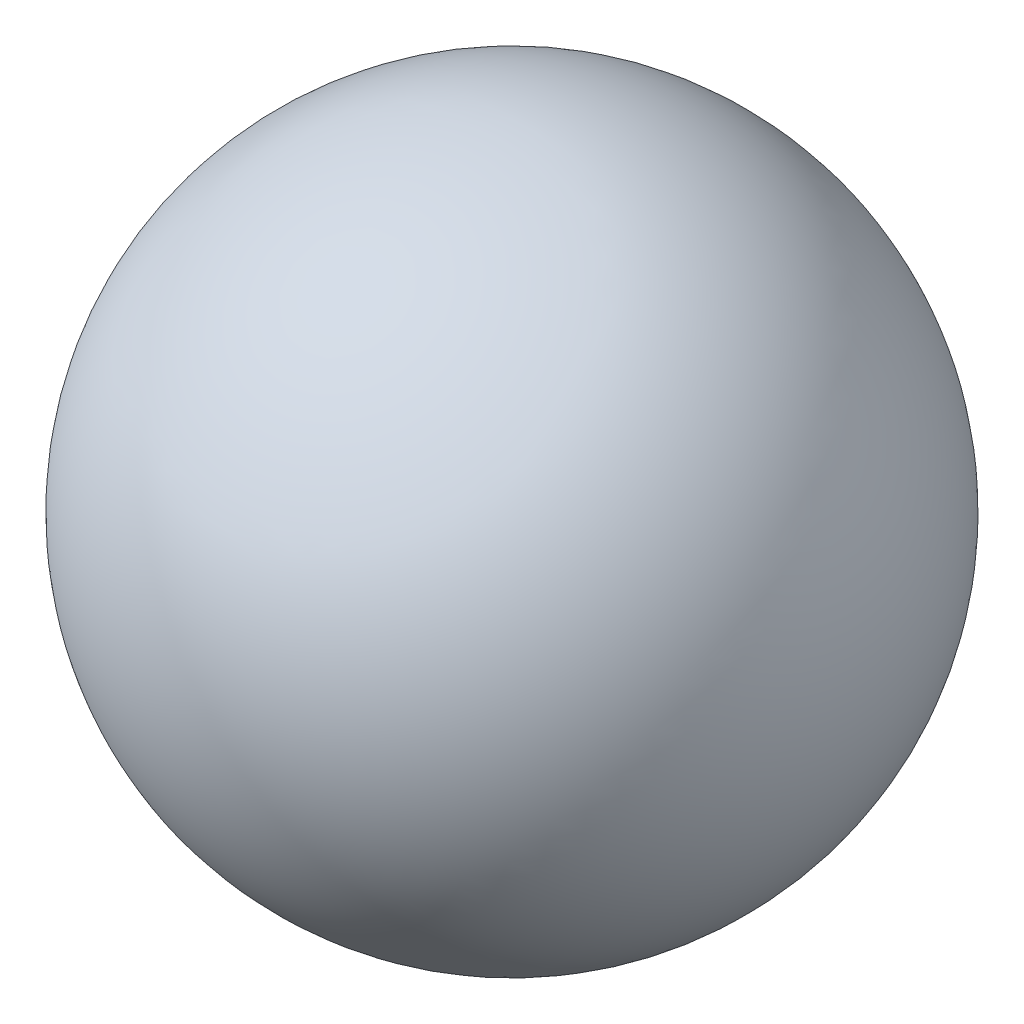
SolidWorks part; units mm, degrees
material "合金钢"
ref_plane "前视基准面" through (0, 0, 0) normal (0, 0, 1) x (1, 0, 0)
ref_plane "上视基准面" through (0, 0, 0) normal (0, 1, 0) x (1, 0, 0)
ref_plane "右视基准面" through (0, 0, 0) normal (1, 0, 0) x (0, 0, -1)
sketch "草图1" plane through (0, 0, 0) normal (0, 1, 0) x (1, 0, 0)
  line L0 (0, 12.115) -> (0, -13.3772) construction
  circle A0 centre (0, 0) radius 8.27
  dimension "D1" = 16.54
revolve "旋转2" add sketch "草图1" angle 360 about L0
